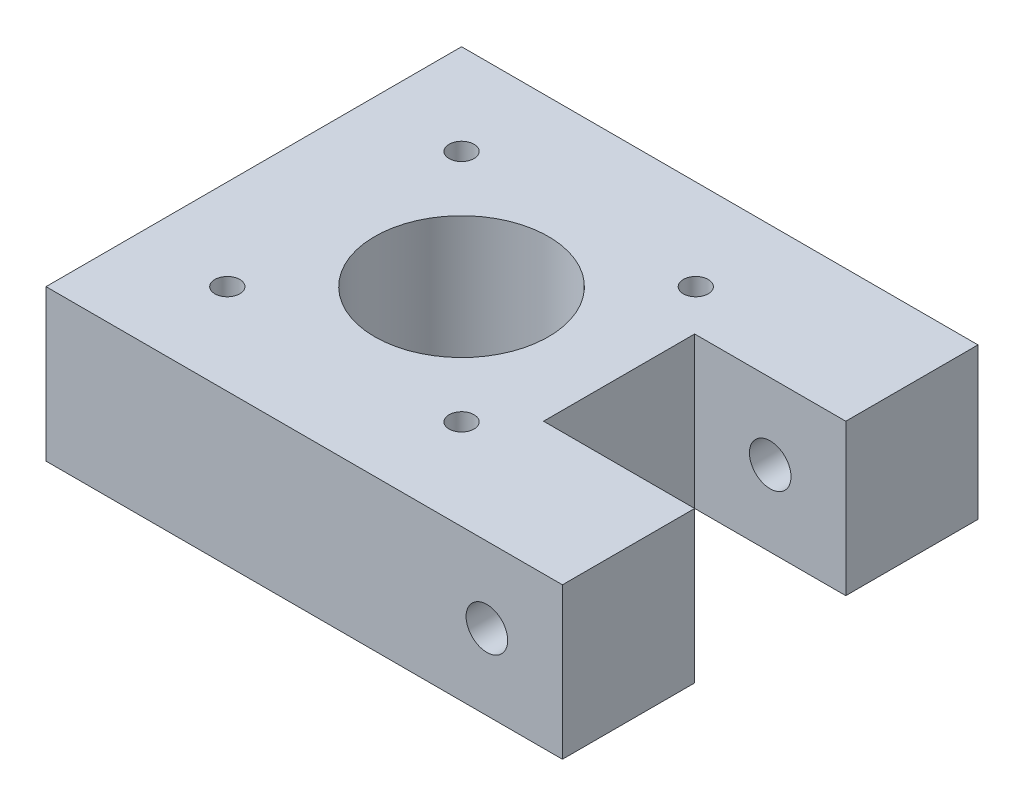
SolidWorks part; units mm, degrees
ref_plane "前视基准面" through (0, 0, 0) normal (0, 0, 1) x (1, 0, 0)
ref_plane "上视基准面" through (0, 0, 0) normal (0, 1, 0) x (1, 0, 0)
ref_plane "右视基准面" through (0, 0, 0) normal (1, 0, 0) x (0, 0, -1)
other "Configuration Table"
sketch "草图1" plane through (0, 0, 0) normal (0, 1, 0) x (1, 0, 0)
  line L0 (20.85, 20.85) -> (20.85, 27.5)
  line L1 (-20.85, 20.85) -> (20.85, 20.85) construction
  line L2 (-20.85, 20.85) -> (-20.85, -20.85) construction
  line L3 (-20.85, -20.85) -> (20.85, -20.85) construction
  line L5 (-20.85, 20.85) -> (20.85, -20.85) construction
  line L6 (-20.85, -20.85) -> (20.85, 20.85) construction
  line L7 (-27.5, 27.5) -> (20.85, 27.5)
  line L8 (-27.5, 27.5) -> (-27.5, -27.5)
  line L9 (-27.5, -27.5) -> (20.85, -27.5)
  line L11 (-27.5, 27.5) -> (20.85, -20.85) construction
  line L12 (-27.5, -27.5) -> (20.85, 20.85) construction
  line L17 (-15.5, 15.5) -> (15.5, 15.5) construction
  line L18 (-15.5, 15.5) -> (-15.5, -15.5) construction
  line L19 (-15.5, -15.5) -> (15.5, -15.5) construction
  line L20 (15.5, 15.5) -> (15.5, -15.5) construction
  line L21 (-15.5, 15.5) -> (15.5, -15.5) construction
  line L22 (-15.5, -15.5) -> (15.5, 15.5) construction
  line L23 (20.85, 20.85) -> (20.85, -27.5)
  circle A0 centre (-15.5, 15.5) radius 1.65
  circle A1 centre (15.5, 15.5) radius 1.65
  circle A2 centre (15.5, -15.5) radius 1.65
  circle A3 centre (-15.5, -15.5) radius 1.65
  circle A4 centre (0, 0) radius 11.5
  point P0 (0, 0)
  point P5 (0, 0)
  point P11 (0, 0)
  dimension "D7" = 3.3
  dimension "D10" = 23
  dimension "D1" = 41.7
  dimension "D2" = 41.7
  dimension "D5" = 31
  dimension "D6" = 31
  dimension "D8" = 2
  dimension "D9" = 2
extrude "凸台-拉伸1" add sketch "草图1" along normal blind 20
sketch "草图6" plane through (20.85, 0, 0) normal (1, 0, 0) x (0, 0, -1)
  line L0 (0, 20) -> (0, 0) construction
  line L1 (-27.5, 20) -> (27.5, 20) construction
  line L3 (-10, 0) -> (10, 0)
  line L4 (-10, 0) -> (-10, 20)
  line L5 (-10, 20) -> (10, 20)
  line L6 (10, 0) -> (10, 20)
  line L7 (-10, 0) -> (10, 20) construction
  line L8 (-10, 20) -> (10, 0) construction
  line L9 (-27.5, 20) -> (27.5, 20)
  line L10 (-27.5, 20) -> (-27.5, 0)
  line L11 (-27.5, 0) -> (27.5, 0)
  line L12 (27.5, 20) -> (27.5, 0)
  point P5 (0, 10)
  line M10 (-27.5, 0) -> (27.5, 0)
  line M11 (27.5, 0) -> (27.5, 20)
  line M12 (27.5, 20) -> (-27.5, 20)
  line M13 (-27.5, 20) -> (-27.5, 0)
  dimension "D1" = 20
extrude "凸台-拉伸2" add sketch "草图6" along normal blind 20 contours L6 M10 M11 M12 | L4 M10 M12 M13
sketch "草图7" plane through (0, 0, 0) normal (0, -1, 0) x (1, 0, 0)
  circle A0 centre (-15.5, 15.5) radius 3
  circle A1 centre (15.5, 15.5) radius 3
  circle A2 centre (15.5, -15.5) radius 3
  circle A3 centre (-15.5, -15.5) radius 3
  dimension "D1" = 6
  dimension "D2" = 2
  dimension "D3" = 2
extrude "切除-拉伸1" cut sketch "草图7" against normal blind 16
sketch "草图8" plane through (0, 0, -27.5) normal (0, 0, -1) x (-1, 0, 0)
  line L1 (-40.85, 20) -> (-20.85, 20) construction
  line L2 (-40.85, 20) -> (-40.85, 0) construction
  line L3 (-40.85, 0) -> (-20.85, 0) construction
  line L4 (-20.85, 20) -> (-20.85, 0) construction
  circle A0 centre (-30.85, 10) radius 2.75
  dimension "D1" = 5.5
extrude "切除-拉伸2" cut sketch "草图8" against normal through all
